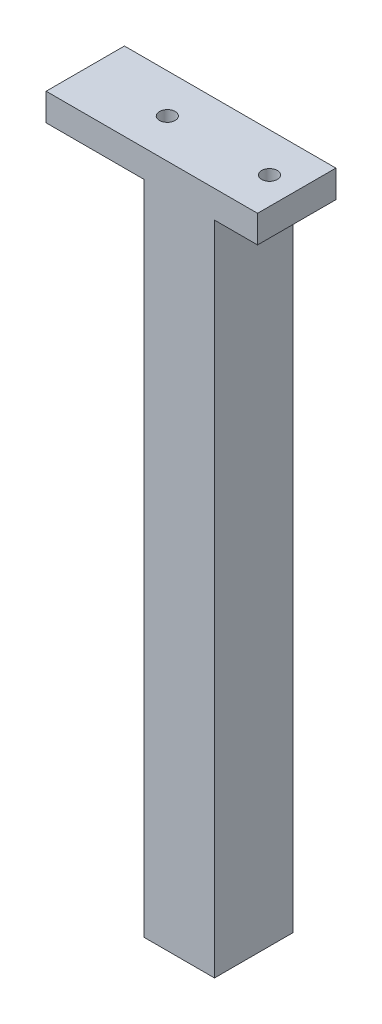
SolidWorks part; units mm, degrees
ref_plane "Front Plane" through (0, 0, 0) normal (0, 0, 1) x (1, 0, 0)
ref_plane "Top Plane" through (0, 0, 0) normal (0, 1, 0) x (1, 0, 0)
ref_plane "Right Plane" through (0, 0, 0) normal (1, 0, 0) x (0, 0, -1)
sketch "Sketch1" plane through (0, 0, 0) normal (0, 1, 0) x (1, 0, 0)
  line L1 (-19.2544, 10.2985) -> (20.7456, 10.2985)
  line L2 (-19.2544, 10.2985) -> (-19.2544, -9.7015)
  line L3 (-19.2544, -9.7015) -> (20.7456, -9.7015)
  line L4 (20.7456, 10.2985) -> (20.7456, -9.7015)
  dimension "D1" = 40
  dimension "D2" = 20
extrude "Boss-Extrude1" add sketch "Sketch1" along normal blind 7
sketch "Sketch2" plane through (0, 7, 0) normal (0, 1, 0) x (1, 0, 0)
  line L0 (-19.2544, 0.2985) -> (20.7456, 0.2985) construction
  line L1 (-19.2544, 10.2985) -> (-19.2544, -9.7015) construction
  line L2 (20.7456, -9.7015) -> (20.7456, 10.2985) construction
  line L3 (0.7456, -9.7015) -> (0.7456, 10.2985) construction
  line L4 (-19.2544, -9.7015) -> (20.7456, -9.7015) construction
  line L5 (20.7456, 10.2985) -> (-19.2544, 10.2985) construction
  circle A0 centre (-12.3044, 0.2985) radius 2
  circle A1 centre (13.7956, 0.2985) radius 2
  dimension "D2" = 4
  dimension "D1" = 26.1
extrude "Cut-Extrude1" cut sketch "Sketch2" against normal through all
sketch "Sketch3" plane through (0, 0, 0) normal (0, -1, 0) x (-1, 0, 0)
  line L0 (-0.7456, -9.7015) -> (-0.7456, 10.2985) construction
  line L1 (8.2544, -9.7015) -> (-9.7456, -9.7015)
  line L2 (8.2544, -9.7015) -> (8.2544, 10.2985)
  line L3 (8.2544, 10.2985) -> (-9.7456, 10.2985)
  line L4 (-9.7456, -9.7015) -> (-9.7456, 10.2985)
  line L5 (19.2544, -9.7015) -> (-20.7456, -9.7015) construction
  line L6 (-20.7456, 10.2985) -> (19.2544, 10.2985) construction
  dimension "D1" = 18
extrude "Boss-Extrude2" add sketch "Sketch3" along normal blind 167.64
sketch "Sketch4" plane through (0, -167.64, 0) normal (0, -1, 0) x (1, 0, 0)
  line L0 (9.7456, 9.7015) -> (-8.2544, 9.7015) construction
  line L1 (-4.2544, 5.7015) -> (5.7456, 5.7015)
  line L2 (-4.2544, 5.7015) -> (-4.2544, -6.2985)
  line L3 (-4.2544, -6.2985) -> (5.7456, -6.2985)
  line L4 (5.7456, 5.7015) -> (5.7456, -6.2985)
  line L5 (9.7456, -10.2985) -> (9.7456, 9.7015) construction
  line L6 (-8.2544, -10.2985) -> (9.7456, -10.2985) construction
  line L7 (-8.2544, 9.7015) -> (-8.2544, -10.2985) construction
  dimension "D1" = 4
  dimension "D2" = 4
  dimension "D3" = 4
  dimension "D4" = 4
extrude "Cut-Extrude2" cut sketch "Sketch4" against normal up to surface (167.64 mm away) up to face at (13.7956, 0, 1.7015)
sketch "Sketch7" plane through (-19.2544, 0, 0) normal (-1, 0, 0) x (0, 0, 1)
  line L4 (-10.2985, 0) -> (9.7015, 0)
  line L5 (9.7015, 0) -> (9.7015, 7)
  line L6 (9.7015, 7) -> (-10.2985, 7)
  line L7 (-10.2985, 7) -> (-10.2985, 0)
  line L8 (-10.2985, 0) -> (9.7015, 0)
  line L9 (9.7015, 0) -> (9.7015, 7)
  line L10 (9.7015, 7) -> (-10.2985, 7)
  line L11 (-10.2985, 7) -> (-10.2985, 0)
  dimension "D1" = 0
extrude "Boss-Extrude3" add sketch "Sketch7" along normal blind 14
